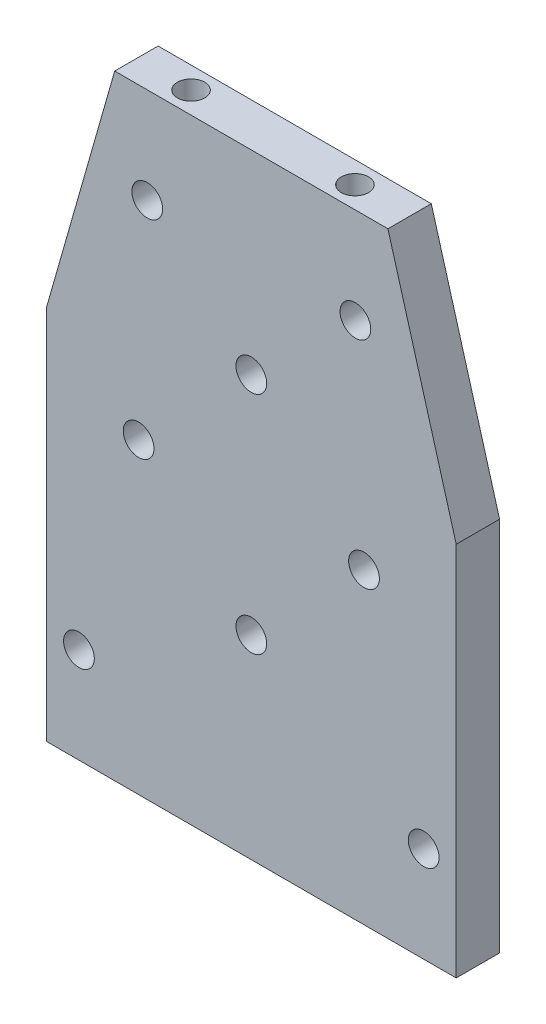
SolidWorks part; units mm, degrees
material "6061 Alloy"
ref_plane "Front Plane" through (0, 0, 0) normal (0, 0, 1) x (1, 0, 0)
ref_plane "Top Plane" through (0, 0, 0) normal (0, 1, 0) x (1, 0, 0)
ref_plane "Right Plane" through (0, 0, 0) normal (1, 0, 0) x (0, 0, -1)
sketch "Sketch1" plane through (0, 0, 0) normal (0, 0, 1) x (1, 0, 0)
  line L0 (-20, 45) -> (20, 45)
  line L5 (-30, -45) -> (30, -45)
  line L6 (0, 45) -> (0, -45) construction
  line L7 (-20, 45) -> (-30, 10)
  line L8 (-30, 10) -> (-30, -45)
  line L9 (30, 10) -> (30, -45)
  line L10 (20, 45) -> (30, 10)
  dimension "D1" = 90
  dimension "D2" = 60
  dimension "D3" = 40
  dimension "D4" = 55
extrude "1/4" add sketch "Sketch1" along normal mid plane 6.35
sketch "Sketch4" plane through (0, 45, 0) normal (0, 1, 0) x (1, 0, 0)
  line L0 (0, -3.175) -> (0, 3.175) construction
  line L1 (0, 0) -> (-12, 0) construction
  line L2 (20, -3.175) -> (-20, -3.175) construction
  line L3 (20, 3.175) -> (-20, 3.175) construction
  circle A0 centre (-12, 0) radius 2
  circle A1 centre (12, 0) radius 2
  dimension "D2" = 4
  dimension "D1" = 12
extrude "M4_DRILL" cut sketch "Sketch4" against normal blind 8
sketch "Sketch5" plane through (0, -45, 0) normal (0, -1, 0) x (-1, 0, 0)
  line L0 (0, -3.175) -> (0, 3.175) construction
  line L2 (0, 0) -> (-20, 0) construction
  line L3 (30, -3.175) -> (-30, -3.175) construction
  line L4 (30, 3.175) -> (-30, 3.175) construction
  circle A0 centre (-20, 0) radius 2
  circle A1 centre (20, 0) radius 2
  circle A2 centre (0, 0) radius 2
  dimension "D1" = 4
  dimension "D2" = 20
extrude "M4_DRILL2" cut sketch "Sketch5" against normal blind 8
sketch "Sketch6" plane through (0, 0, 3.175) normal (0, 0, 1) x (1, 0, 0)
  line L0 (-30, -45) -> (30, -45) construction
  line L1 (-30, 10) -> (-30, -45) construction
  line L2 (0, 0) -> (0, -17.9243) construction
  line L3 (20, 45) -> (-20, 45) construction
  circle A0 centre (-25.2375, -31) radius 2.25
  circle A1 centre (25.2375, -31) radius 2.25
  circle A2 centre (-15.2375, 31) radius 2.25
  circle A3 centre (15.2375, 31) radius 2.25
  dimension "D1" = 4.5
  dimension "D6" = 4.5
  dimension "D2" = 14
  dimension "D3" = 4.7625
  dimension "D4" = 14
  dimension "D5" = 4.7625
extrude "M4_through" cut sketch "Sketch6" against normal up to surface (6.35 mm away) up to face at (0, 3.3333, -3.175)
sketch "Sketch8" plane through (0, 0, -3.175) normal (0, 0, -1) x (-1, 0, 0)
  circle A0 centre (0, 0) radius 16.5 construction
  circle A1 centre (0, 16.5) radius 2.25
  circle A2 centre (16.5, 0) radius 2.25
  circle A3 centre (0, -16.5) radius 2.25
  circle A4 centre (-16.5, 0) radius 2.25
  point P14 (0, 0)
  dimension "D1" = 33
  dimension "D2" = 4.5
  dimension "D3" = 4
extrude "M4_through2" cut sketch "Sketch8" against normal blind 10
